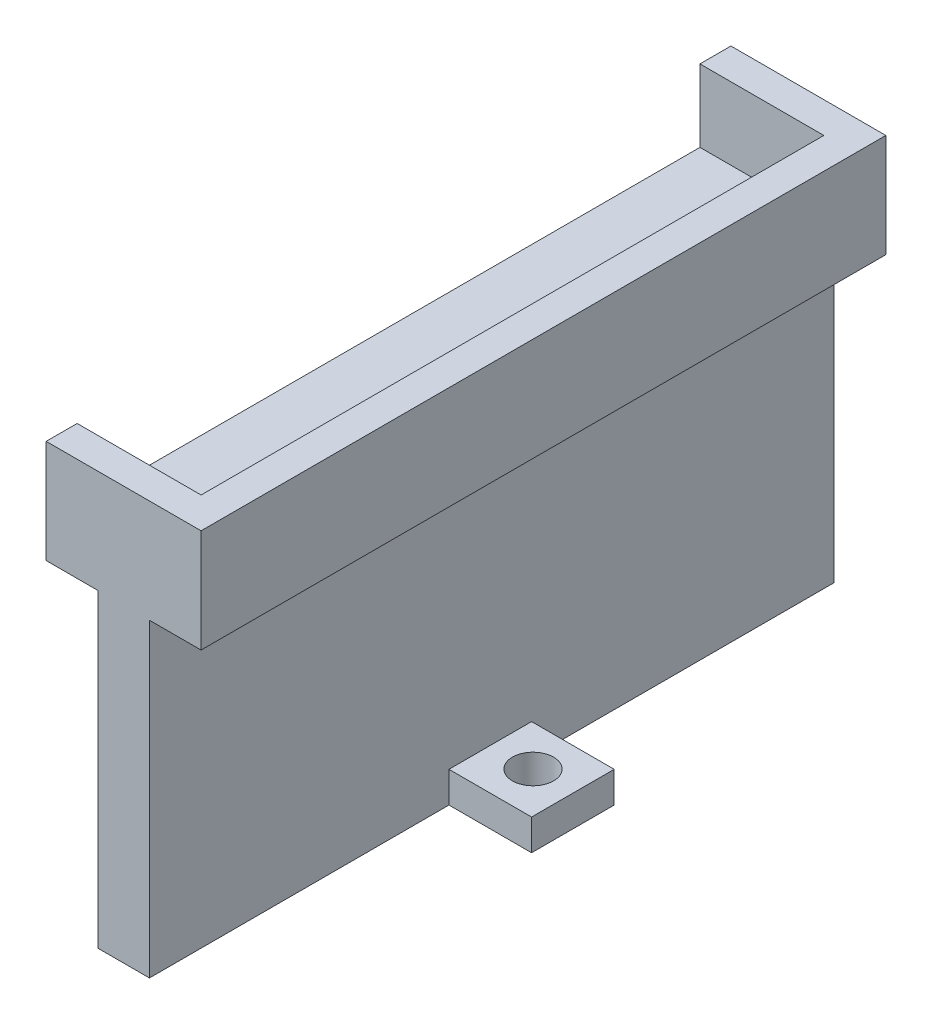
SolidWorks part; units mm, degrees
ref_plane "Front Plane" through (0, 0, 0) normal (0, 0, 1) x (1, 0, 0)
ref_plane "Top Plane" through (0, 0, 0) normal (0, 1, 0) x (1, 0, 0)
ref_plane "Right Plane" through (0, 0, 0) normal (1, 0, 0) x (0, 0, -1)
sketch "Sketch1" plane through (0, 0, 0) normal (0, 1, 0) x (1, 0, 0)
  line L1 (64.0039, -39.1135) -> (-112.9961, -39.1135)
  line L2 (64.0039, -39.1135) -> (64.0039, 27.1865)
  line L3 (64.0039, 27.1865) -> (-112.9961, 27.1865)
  line L4 (-112.9961, -39.1135) -> (-112.9961, 27.1865)
  line L5 (64.0039, -39.1135) -> (-112.9961, 27.1865) construction
  line L6 (64.0039, 27.1865) -> (-112.9961, -39.1135) construction
  point P0 (-24.4961, -5.9635)
  point P5 (0, 0.6131)
extrude "Boss-Extrude1" add sketch "Sketch1" along normal blind 10
sketch "Sketch2" plane through (0, 10, 0) normal (0, 1, 0) x (1, 0, 0)
  line L0 (-112.9961, -39.1135) -> (64.0039, -39.1135) construction
  line L1 (61.0039, -36.1135) -> (-109.9961, -36.1135)
  line L2 (61.0039, -36.1135) -> (61.0039, 24.1865)
  line L3 (61.0039, 24.1865) -> (-109.9961, 24.1865)
  line L4 (-109.9961, -36.1135) -> (-109.9961, 24.1865)
  line L5 (61.0039, -36.1135) -> (-109.9961, 24.1865) construction
  line L6 (61.0039, 24.1865) -> (-109.9961, -36.1135) construction
  line L7 (64.0039, -39.1135) -> (64.0039, 27.1865) construction
  point P0 (-24.4961, -5.9635)
  dimension "D1" = 3
  dimension "D2" = 3
extrude "Cut-Extrude1" cut sketch "Sketch2" against normal blind 7 and the other way through all
sketch "Sketch3" plane through (0, 0, 0) normal (0, -1, 0) x (1, 0, 0)
  line L0 (-112.9961, 39.1135) -> (64.0039, 39.1135) construction
  line L1 (-107.9961, 39.1135) -> (-102.9961, 39.1135)
  line L2 (-107.9961, 39.1135) -> (-107.9961, -27.1865)
  line L3 (-107.9961, -27.1865) -> (-102.9961, -27.1865)
  line L4 (-102.9961, 39.1135) -> (-102.9961, -27.1865)
  line L5 (-107.9961, 39.1135) -> (-102.9961, -27.1865) construction
  line L6 (-107.9961, -27.1865) -> (-102.9961, 39.1135) construction
  line L7 (54.0039, 39.1135) -> (59.0039, 39.1135)
  line L8 (54.0039, 39.1135) -> (54.0039, -27.1865)
  line L9 (54.0039, -27.1865) -> (59.0039, -27.1865)
  line L10 (59.0039, 39.1135) -> (59.0039, -27.1865)
  line L11 (54.0039, 39.1135) -> (59.0039, -27.1865) construction
  line L12 (54.0039, -27.1865) -> (59.0039, 39.1135) construction
  line L13 (64.0039, -27.1865) -> (-112.9961, -27.1865) construction
  line L14 (-112.9961, -27.1865) -> (-112.9961, 39.1135) construction
  line L15 (64.0039, 39.1135) -> (64.0039, -27.1865) construction
  point P0 (-105.4961, 5.9635)
  point P5 (56.5039, 5.9635)
  dimension "D1" = 0
  dimension "D2" = 0
  dimension "D3" = 0
  dimension "D4" = 0
  dimension "D5" = 5
  dimension "D6" = 5
  dimension "D7" = 5
extrude "Boss-Extrude2" add sketch "Sketch3" along normal blind 30
sketch "Sketch4" plane through (0, 0, 0) normal (0, -1, 0) x (1, 0, 0)
  line L0 (-102.9961, 39.1135) -> (54.0039, 39.1135) construction
  line L1 (49.0039, -27.1865) -> (-97.9961, -27.1865)
  line L2 (49.0039, -27.1865) -> (49.0039, 39.1135)
  line L3 (49.0039, 39.1135) -> (-97.9961, 39.1135)
  line L4 (-97.9961, -27.1865) -> (-97.9961, 39.1135)
  line L5 (49.0039, -27.1865) -> (-97.9961, 39.1135) construction
  line L6 (49.0039, 39.1135) -> (-97.9961, -27.1865) construction
  line L7 (54.0039, -27.1865) -> (-102.9961, -27.1865) construction
  line L8 (-102.9961, -27.1865) -> (-102.9961, 39.1135) construction
  line L9 (54.0039, 39.1135) -> (54.0039, -27.1865) construction
  point P0 (-24.4961, 5.9635)
  dimension "D1" = 0
  dimension "D2" = 0
  dimension "D3" = 5
  dimension "D4" = 5
extrude "Cut-Extrude2" cut sketch "Sketch4" against normal blind 30
sketch "Sketch5" plane through (0, -30, 0) normal (0, -1, 0) x (1, 0, 0)
  line L0 (-107.9961, 39.1135) -> (-107.9961, -27.1865) construction
  line L1 (-107.9961, 2.1135) -> (-115.9961, 2.1135)
  line L2 (-107.9961, 2.1135) -> (-107.9961, 10.1135)
  line L3 (-107.9961, 10.1135) -> (-115.9961, 10.1135)
  line L4 (-115.9961, 2.1135) -> (-115.9961, 10.1135)
  line L5 (-107.9961, 2.1135) -> (-115.9961, 10.1135) construction
  line L6 (-107.9961, 10.1135) -> (-115.9961, 2.1135) construction
  line L7 (67.0039, 2.1135) -> (59.0039, 2.1135)
  line L8 (67.0039, 2.1135) -> (67.0039, 10.1135)
  line L9 (67.0039, 10.1135) -> (59.0039, 10.1135)
  line L10 (59.0039, 2.1135) -> (59.0039, 10.1135)
  line L11 (67.0039, 2.1135) -> (59.0039, 10.1135) construction
  line L12 (67.0039, 10.1135) -> (59.0039, 2.1135) construction
  line L13 (59.0039, -27.1865) -> (59.0039, 39.1135) construction
  line L14 (-112.9961, 39.1135) -> (-107.9961, 39.1135) construction
  line L15 (59.0039, 39.1135) -> (64.0039, 39.1135) construction
  circle A0 centre (-111.977, 5.9964) radius 1.8999
  circle A1 centre (63.046, 6.0212) radius 1.9942
  point P0 (-111.9961, 6.1135)
  point P5 (63.0039, 6.1135)
  dimension "D1" = 0
  dimension "D2" = 0
  dimension "D3" = 29
  dimension "D4" = 29
  dimension "D5" = 4
  dimension "D6" = 4
extrude "Boss-Extrude3" add sketch "Sketch5" against normal blind 3
sketch "Sketch6" plane through (0, 0, -27.1865) normal (0, 0, -1) x (-1, 0, 0)
  line L1 (68.5577, 75.1964) -> (121.7583, 75.1964)
  line L2 (68.5577, 75.1964) -> (68.5577, -43.2789)
  line L3 (68.5577, -43.2789) -> (121.7583, -43.2789)
  line L4 (121.7583, 75.1964) -> (121.7583, -43.2789)
  line L5 (68.5577, 75.1964) -> (121.7583, -43.2789) construction
  line L6 (68.5577, -43.2789) -> (121.7583, 75.1964) construction
  point P0 (95.158, 15.9587)
extrude "Cut-Extrude3" cut sketch "Sketch6" against normal through all
